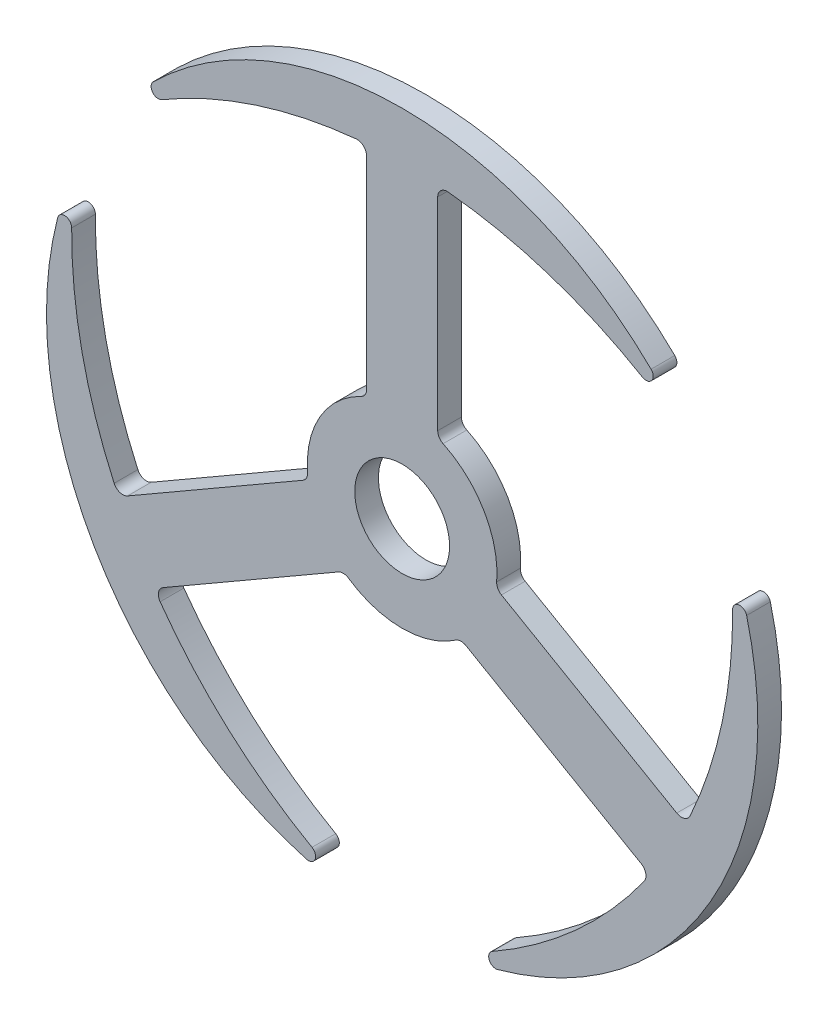
SolidWorks part; units mm, degrees
material "Литая легированная сталь"
ref_plane "Спереди" through (0, 0, 0) normal (0, 0, 1) x (1, 0, 0)
ref_plane "Сверху" through (0, 0, 0) normal (0, 1, 0) x (1, 0, 0)
ref_plane "Справа" through (0, 0, 0) normal (1, 0, 0) x (0, 0, -1)
sketch "Эскиз1" plane through (0, 0, 0) normal (0, 0, 1) x (1, 0, 0)
  line L0 (0, 0) -> (0, 7.5) construction
  line L1 (-6, 4.5) -> (6, 4.5) construction
  line L2 (-0.75, 6.2538) -> (-0.75, 1.9843)
  line L3 (0.75, 6.2538) -> (0.75, 1.9843)
  line L4 (5.791, -2.4774) -> (2.0935, -0.3426)
  line L5 (5.041, -3.7764) -> (1.3435, -1.6417)
  line L6 (6.8971, 2.9462) -> (0.8971, -7.4462) construction
  line L7 (-5.041, -3.7764) -> (-1.3435, -1.6417)
  line L8 (-5.791, -2.4774) -> (-2.0935, -0.3426)
  line L9 (-0.8971, -7.4462) -> (-6.8971, 2.9462) construction
  arc A0 (5.2489, 5.3571) -> (-5.2489, 5.3571) centre (0, 0) ccw
  circle A1 centre (0, 0) radius 1
  arc A2 (-0.75, 6.4566) -> (0.75, 6.4566) centre (0, 0) ccw construction
  arc A3 (-5.0679, 5.1207) -> (-0.9694, 6.4529) centre (0, -3.5) cw
  circle A4 centre (0, 0) radius 7.5 construction
  arc A5 (5.2489, 5.3571) -> (5.0679, 5.1207) centre (5.1439, 5.25) cw
  arc A6 (-5.0679, 5.1207) -> (-5.2489, 5.3571) centre (-5.1439, 5.25) cw
  arc A7 (-0.8636, 1.8039) -> (-1.9941, -0.154) centre (0, 0) ccw
  arc A8 (0.9694, 6.4529) -> (5.0679, 5.1207) centre (0, -3.5) cw
  circle A9 centre (0, 0) radius 6.5 construction
  arc A10 (0.9694, 6.4529) -> (0.75, 6.2538) centre (0.95, 6.2538) ccw
  arc A11 (0.75, 1.9843) -> (0.8636, 1.8039) centre (0.95, 1.9843) ccw
  arc A12 (-0.75, 1.9843) -> (-0.8636, 1.8039) centre (-0.95, 1.9843) cw
  arc A13 (-0.75, 6.2538) -> (-0.9694, 6.4529) centre (-0.95, 6.2538) ccw
  arc A14 (2.015, -7.2243) -> (7.2639, 1.8671) centre (0, 0) ccw
  arc A15 (6.9686, 1.8286) -> (6.0731, -2.3869) centre (-3.0311, 1.75) cw
  arc A16 (2.015, -7.2243) -> (1.9007, -6.9493) centre (1.9747, -7.0798) cw
  arc A17 (6.9686, 1.8286) -> (7.2639, 1.8671) centre (7.1186, 1.8298) cw
  arc A18 (5.1037, -4.066) -> (1.9007, -6.9493) centre (-3.0311, 1.75) cw
  arc A19 (5.1037, -4.066) -> (5.041, -3.7764) centre (4.941, -3.9496) ccw
  arc A20 (1.3435, -1.6417) -> (1.1304, -1.6499) centre (1.2435, -1.8149) ccw
  arc A21 (2.0935, -0.3426) -> (1.9941, -0.154) centre (2.1935, -0.1694) cw
  arc A22 (5.791, -2.4774) -> (6.0731, -2.3869) centre (5.891, -2.3042) ccw
  arc A23 (-7.2639, 1.8671) -> (-2.015, -7.2243) centre (0, 0) ccw
  arc A24 (-1.9007, -6.9493) -> (-5.1037, -4.066) centre (3.0311, 1.75) cw
  arc A25 (-7.2639, 1.8671) -> (-6.9686, 1.8286) centre (-7.1186, 1.8298) cw
  arc A26 (-1.9007, -6.9493) -> (-2.015, -7.2243) centre (-1.9747, -7.0798) cw
  arc A27 (-6.0731, -2.3869) -> (-6.9686, 1.8286) centre (3.0311, 1.75) cw
  arc A28 (-6.0731, -2.3869) -> (-5.791, -2.4774) centre (-5.891, -2.3042) ccw
  arc A29 (-2.0935, -0.3426) -> (-1.9941, -0.154) centre (-2.1935, -0.1694) ccw
  arc A30 (-1.3435, -1.6417) -> (-1.1304, -1.6499) centre (-1.2435, -1.8149) cw
  arc A31 (-5.041, -3.7764) -> (-5.1037, -4.066) centre (-4.941, -3.9496) ccw
  arc A32 (1.9941, -0.154) -> (0.8636, 1.8039) centre (0, 0) ccw
  arc A33 (-1.1304, -1.6499) -> (1.1304, -1.6499) centre (0, 0) ccw
  point P24 (0.75, 6.4718)
  point P27 (0.75, 1.854)
  point P30 (-0.75, 1.854)
  point P33 (-0.75, 6.4718)
  point P78 (0, 0)
  dimension "D1" = 15
  dimension "D2" = 2
  dimension "D5" = 0.15
  dimension "D6" = 4
  dimension "D8" = 0.2
  dimension "D4" = 12
  dimension "D7" = 1.5
  dimension "D3" = 1
  dimension "D9" = 3
extrude "Бобышка-Вытянуть2" add sketch "Эскиз1" along normal blind 0.5
